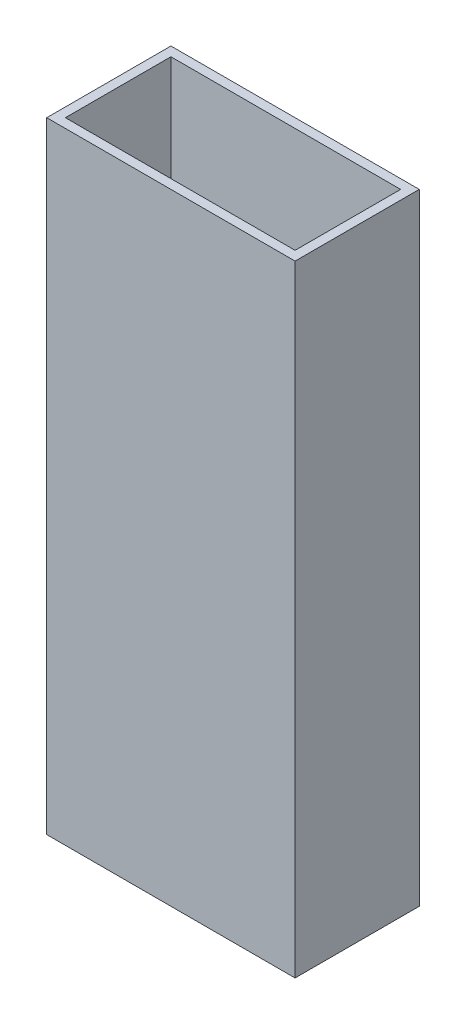
SolidWorks part; units mm, degrees
ref_plane "Front Plane" through (0, 0, 0) normal (0, 0, 1) x (1, 0, 0)
ref_plane "Top Plane" through (0, 0, 0) normal (0, 1, 0) x (1, 0, 0)
ref_plane "Right Plane" through (0, 0, 0) normal (1, 0, 0) x (0, 0, -1)
sketch "Sketch1" plane through (0, 0, 0) normal (0, 1, 0) x (1, 0, 0)
  line L1 (-20, -10) -> (20, -10)
  line L2 (-20, -10) -> (-20, 10)
  line L3 (-20, 10) -> (20, 10)
  line L4 (20, -10) -> (20, 10)
  line L5 (0, 10) -> (0, -10) construction
  line L6 (-20, 0) -> (20, 0) construction
  line L7 (18.5, -8.5) -> (-18.5, -8.5)
  line L8 (18.5, -8.5) -> (18.5, 8.5)
  line L9 (18.5, 8.5) -> (-18.5, 8.5)
  line L10 (-18.5, -8.5) -> (-18.5, 8.5)
  line L11 (0, 8.5) -> (0, -8.5) construction
  line L12 (18.5, 0) -> (-18.5, 0) construction
  point P0 (0, 0)
  point P4 (0, 0)
  dimension "D1" = 40
  dimension "D2" = 20
  dimension "D3" = 37
  dimension "D4" = 17
extrude "Boss-Extrude1" add sketch "Sketch1" along normal blind 100
